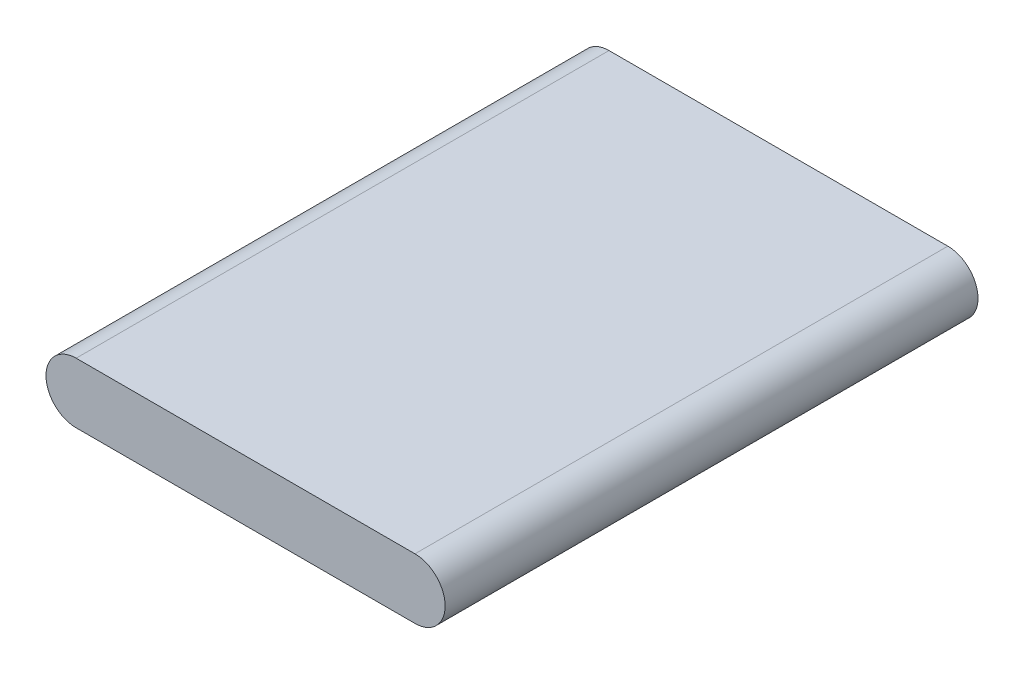
SolidWorks part; units mm, degrees
ref_plane "前视基准面" through (0, 0, 0) normal (0, 0, 1) x (1, 0, 0)
ref_plane "上视基准面" through (0, 0, 0) normal (0, 1, 0) x (1, 0, 0)
ref_plane "右视基准面" through (0, 0, 0) normal (1, 0, 0) x (0, 0, -1)
sketch "草图1" plane through (0, 0, 0) normal (0, 0, 1) x (1, 0, 0)
  line L0 (-16.85, 0) -> (16.85, 0) construction
  line L1 (-16.85, 3) -> (16.85, 3)
  line L2 (-16.85, -3) -> (16.85, -3)
  arc A0 (-16.85, 3) -> (-16.85, -3) centre (-16.85, 0) ccw
  arc A1 (16.85, -3) -> (16.85, 3) centre (16.85, 0) ccw
  point P2 (0, 0)
  dimension "D1" = 3
  dimension "D2" = 33.7
extrude "凸台-拉伸1" add sketch "草图1" along normal blind 53
